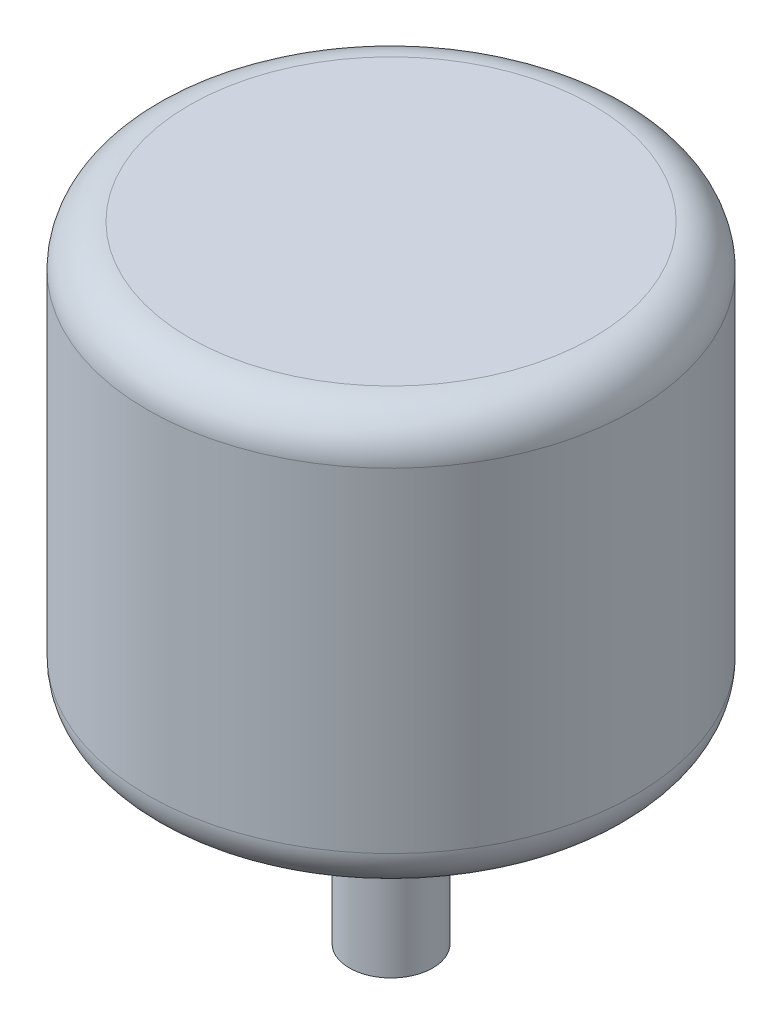
SolidWorks part; units mm, degrees
ref_plane "前视基准面" through (0, 0, 0) normal (0, 0, 1) x (1, 0, 0)
ref_plane "上视基准面" through (0, 0, 0) normal (0, 1, 0) x (1, 0, 0)
ref_plane "右视基准面" through (0, 0, 0) normal (1, 0, 0) x (0, 0, -1)
other "Configuration Table"
sketch "草图1" plane through (0, 0, 0) normal (0, 1, 0) x (1, 0, 0)
  circle A0 centre (0, 0) radius 17.5
  dimension "D1" = 35
extrude "凸台-拉伸1" add sketch "草图1" along normal blind 30 contours A0
sketch "草图2" plane through (0, 0, 0) normal (0, -1, 0) x (-1, 0, 0)
  circle A0 centre (0, 0) radius 3
  dimension "D1" = 6
extrude "凸台-拉伸2" add sketch "草图2" along normal blind 15
fillet "圆角1" radius 3 2 edges at (0, 30, 17.5) (0, 0, 17.5)
extrude "切除-拉伸1" cut sketch "草图3" against normal blind 10
sketch "草图3" plane through (929.367, -2, 420.3298) normal (0, -1, 0) x (-0.911, 0, -0.4125)
  circle A0 centre (1012, -0.4489) radius 1.5
  circle A1 centre (1020, 7.5511) radius 1.5
  circle A2 centre (1028, -0.4489) radius 1.5
  circle A3 centre (1020, -8.4489) radius 1.5
  point P14 (1020, -0.4489)
